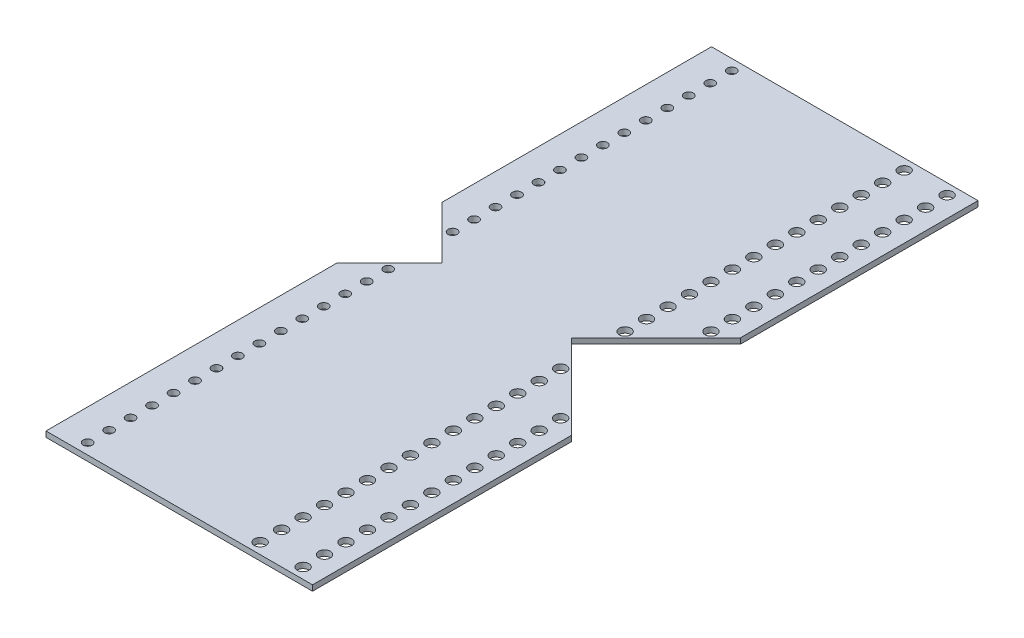
SolidWorks part; units mm, degrees
ref_plane "Front Plane" through (0, 0, 0) normal (0, 0, 1) x (1, 0, 0)
ref_plane "Top Plane" through (0, 0, 0) normal (0, 1, 0) x (1, 0, 0)
ref_plane "Right Plane" through (0, 0, 0) normal (1, 0, 0) x (0, 0, -1)
sketch "Sketch1" plane through (0, 0, 0) normal (0, 1, 0) x (1, 0, 0)
  line L0 (44.2429, -38.9911) -> (44.2429, -192.2393)
  line L1 (-113.42, 201.4607) -> (-82.3339, 201.4607)
  line L2 (-113.42, 201.4607) -> (-113.42, 42.0468)
  line L3 (-117.23, -192.2393) -> (44.2429, -192.2393)
  line L4 (44.2429, 201.4607) -> (44.2429, 60.9125)
  line L5 (-82.3339, 201.4607) -> (44.2429, 201.4607)
  line L9 (-82.432, 11.0588) -> (-82.432, -192.2393)
  line L15 (-82.3339, 201.4607) -> (-82.3339, 10.9607)
  line L17 (-5.7089, 10.9607) -> (44.2429, 60.9125)
  line L19 (-5.7089, 10.9607) -> (44.2429, -38.9911)
  line L21 (-5.724, 201.4607) -> (-5.724, -192.2393)
  line L25 (-82.3339, 10.9607) -> (-113.42, 42.0468)
  line L26 (-82.3339, 10.9607) -> (-113.42, -20.1254)
  line L27 (-113.42, -20.1254) -> (-113.42, -192.2393)
  line L28 (-82.432, 10.9607) -> (-5.7089, 10.9607)
  circle A0 centre (-95.132, 195.1107) radius 2.667
  circle A1 centre (6.9049, 195.1107) radius 3.4365
  circle A2 centre (-95.132, 182.4107) radius 2.667
  circle A3 centre (-95.132, 169.7107) radius 2.667
  circle A4 centre (-95.132, 157.0107) radius 2.667
  circle A5 centre (-95.132, 144.3107) radius 2.667
  circle A6 centre (-95.132, 131.6107) radius 2.667
  circle A7 centre (-95.132, 118.9107) radius 2.667
  circle A8 centre (-95.132, 106.2107) radius 2.667
  circle A9 centre (-95.132, 93.5107) radius 2.667
  circle A10 centre (-95.132, 80.8107) radius 2.667
  circle A11 centre (-95.132, 68.1107) radius 2.667
  circle A12 centre (-95.132, 55.4107) radius 2.667
  circle A13 centre (-95.132, 42.7107) radius 2.667
  circle A14 centre (-95.132, 30.0107) radius 2.667
  circle A15 centre (-95.132, 17.3107) radius 2.667 [skipped]
  circle A16 centre (-95.132, 4.6107) radius 2.667 [skipped]
  circle A17 centre (-95.132, -8.0893) radius 2.667
  circle A18 centre (-95.132, -20.7893) radius 2.667
  circle A19 centre (-95.132, -33.4893) radius 2.667
  circle A20 centre (-95.132, -46.1893) radius 2.667
  circle A21 centre (-95.132, -58.8893) radius 2.667
  circle A22 centre (-95.132, -71.5893) radius 2.667
  circle A23 centre (-95.132, -84.2893) radius 2.667
  circle A24 centre (-95.132, -96.9893) radius 2.667
  circle A25 centre (-95.132, -109.6893) radius 2.667
  circle A26 centre (-95.132, -122.3893) radius 2.667
  circle A27 centre (-95.132, -135.0893) radius 2.667
  circle A28 centre (-95.132, -147.7893) radius 2.667
  circle A29 centre (-95.132, -160.4893) radius 2.667
  circle A30 centre (-95.132, -173.1893) radius 2.667
  circle A31 centre (-95.132, -185.8893) radius 2.667
  circle A32 centre (32.3049, 195.1107) radius 3.4365
  circle A33 centre (32.3049, 182.4107) radius 3.4365
  circle A34 centre (32.3049, 169.7107) radius 3.4365
  circle A35 centre (32.3049, 157.0107) radius 3.4365
  circle A36 centre (32.3049, 144.3107) radius 3.4365
  circle A37 centre (32.3049, 131.6107) radius 3.4365
  circle A38 centre (32.3049, 118.9107) radius 3.4365
  circle A39 centre (32.3049, 106.2107) radius 3.4365
  circle A40 centre (32.3049, 93.5107) radius 3.4365
  circle A41 centre (32.3049, 80.8107) radius 3.4365
  circle A42 centre (32.3049, 68.1107) radius 3.4365
  circle A43 centre (32.3049, 55.4107) radius 3.4365
  circle A44 centre (32.3049, 42.7107) radius 3.4365 [skipped]
  circle A45 centre (32.3049, 30.0107) radius 3.4365 [skipped]
  circle A46 centre (32.3049, 17.3107) radius 3.4365 [skipped]
  circle A47 centre (32.3049, 4.6107) radius 3.4365 [skipped]
  circle A48 centre (32.3049, -8.0893) radius 3.4365 [skipped]
  circle A49 centre (32.3049, -20.7893) radius 3.4365 [skipped]
  circle A50 centre (32.3049, -33.4893) radius 3.4365
  circle A51 centre (32.3049, -46.1893) radius 3.4365
  circle A52 centre (32.3049, -58.8893) radius 3.4365
  circle A53 centre (32.3049, -71.5893) radius 3.4365
  circle A54 centre (32.3049, -84.2893) radius 3.4365
  circle A55 centre (32.3049, -96.9893) radius 3.4365
  circle A56 centre (32.3049, -109.6893) radius 3.4365
  circle A57 centre (32.3049, -122.3893) radius 3.4365
  circle A58 centre (32.3049, -135.0893) radius 3.4365
  circle A59 centre (32.3049, -147.7893) radius 3.4365
  circle A60 centre (32.3049, -160.4893) radius 3.4365
  circle A61 centre (32.3049, -173.1893) radius 3.4365
  circle A62 centre (32.3049, -185.8893) radius 3.4365
  circle A63 centre (6.9049, 182.4107) radius 3.4365
  circle A64 centre (6.9049, 169.7107) radius 3.4365
  circle A65 centre (6.9049, 157.0107) radius 3.4365
  circle A66 centre (6.9049, 144.3107) radius 3.4365
  circle A67 centre (6.9049, 131.6107) radius 3.4365
  circle A68 centre (6.9049, 118.9107) radius 3.4365
  circle A69 centre (6.9049, 106.2107) radius 3.4365
  circle A70 centre (6.9049, 93.5107) radius 3.4365
  circle A71 centre (6.9049, 80.8107) radius 3.4365
  circle A72 centre (6.9049, 68.1107) radius 3.4365
  circle A73 centre (6.9049, 55.4107) radius 3.4365
  circle A74 centre (6.9049, 42.7107) radius 3.4365
  circle A75 centre (6.9049, 30.0107) radius 3.4365
  circle A76 centre (6.9049, 17.3107) radius 3.4365 [skipped]
  circle A77 centre (6.9049, 4.6107) radius 3.4365 [skipped]
  circle A78 centre (6.9049, -8.0893) radius 3.4365
  circle A79 centre (6.9049, -20.7893) radius 3.4365
  circle A80 centre (6.9049, -33.4893) radius 3.4365
  circle A81 centre (6.9049, -46.1893) radius 3.4365
  circle A82 centre (6.9049, -58.8893) radius 3.4365
  circle A83 centre (6.9049, -71.5893) radius 3.4365
  circle A84 centre (6.9049, -84.2893) radius 3.4365
  circle A85 centre (6.9049, -96.9893) radius 3.4365
  circle A86 centre (6.9049, -109.6893) radius 3.4365
  circle A87 centre (6.9049, -122.3893) radius 3.4365
  circle A88 centre (6.9049, -135.0893) radius 3.4365
  circle A89 centre (6.9049, -147.7893) radius 3.4365
  circle A90 centre (6.9049, -160.4893) radius 3.4365
  circle A91 centre (6.9049, -173.1893) radius 3.4365
  circle A92 centre (6.9049, -185.8893) radius 3.4365
  dimension "D8" = 393.7
  dimension "D2" = 31
  dimension "D3" = 157.663
  dimension "D4" = 30.988
  dimension "D5" = 49.967
  dimension "D6" = 2
  dimension "D7" = 31
  dimension "D10" = 76.708
extrude "Boss-Extrude1" add sketch "Sketch1" along normal blind 3.302
